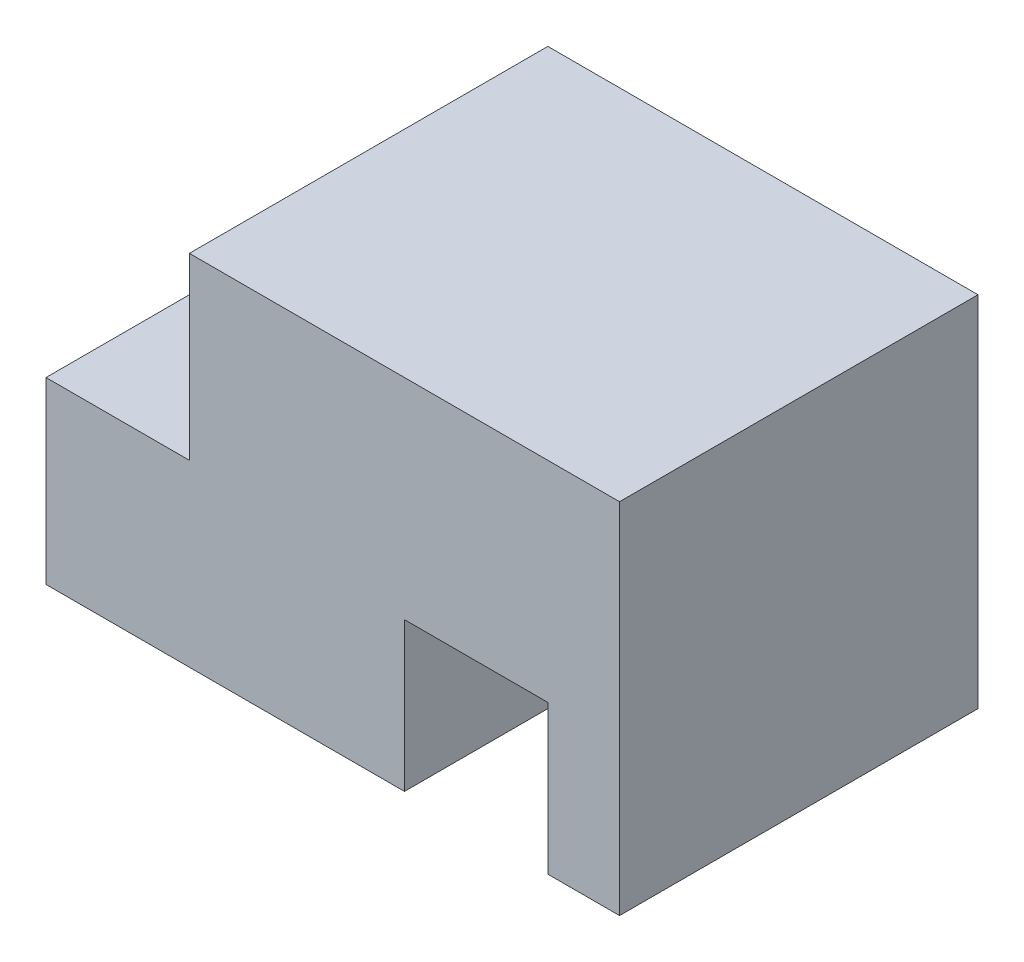
SolidWorks part; units mm, degrees
ref_plane "Ön Düzlem" through (0, 0, 0) normal (0, 0, 1) x (1, 0, 0)
ref_plane "Üst Düzlem" through (0, 0, 0) normal (0, 1, 0) x (1, 0, 0)
ref_plane "Sağ Düzlem" through (0, 0, 0) normal (1, 0, 0) x (0, 0, -1)
sketch "Çizim1" plane through (0, 0, 0) normal (0, 0, 1) x (1, 0, 0)
  line L0 (-1241.7588, -670.9434) -> (-987.7588, -670.9434)
  line L1 (-2511.7588, 599.0566) -> (-987.7588, 599.0566)
  line L2 (-2511.7588, 599.0566) -> (-2511.7588, -35.9434)
  line L4 (-987.7588, 599.0566) -> (-987.7588, -570.3019)
  line L5 (-3019.7588, -35.9434) -> (-2511.7588, -35.9434)
  line L6 (-3019.7588, -35.9434) -> (-3019.7588, -670.9434)
  line L7 (-3019.7588, -670.9434) -> (-1749.7588, -670.9434)
  line L8 (-987.7588, -570.3019) -> (-987.7588, -670.9434)
  line L9 (-1749.7588, -143.7736) -> (-1241.7588, -143.7736)
  line L10 (-1749.7588, -143.7736) -> (-1749.7588, -670.9434)
  line L12 (-1241.7588, -143.7736) -> (-1241.7588, -670.9434)
  dimension "D1" = 1524
  dimension "D2" = 1270
  dimension "D3" = 1270
  dimension "D4" = 254
  dimension "D5" = 635
  dimension "D6" = 508
extrude "Yükseklik-Ekstrüzyon1" add sketch "Çizim1" along normal blind 1270
